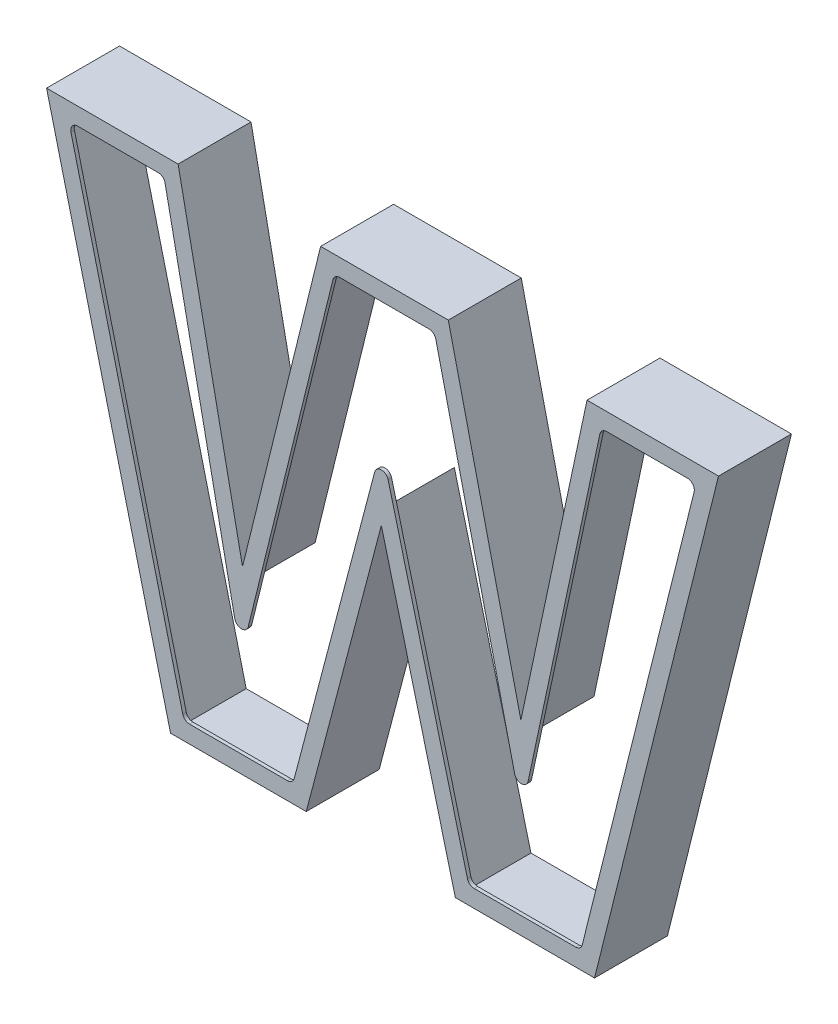
SolidWorks part; units mm, degrees
ref_plane "Front Plane" through (0, 0, 0) normal (0, 0, 1) x (1, 0, 0)
ref_plane "Top Plane" through (0, 0, 0) normal (0, 1, 0) x (1, 0, 0)
ref_plane "Right Plane" through (0, 0, 0) normal (1, 0, 0) x (0, 0, -1)
sketch "Sketch1" plane through (0, 0, 0) normal (0, 0, 1) x (1, 0, 0)
  line L104 (2646.8216, -1645.5826) -> (2668.4435, -1563.4302)
  line L105 (2668.4435, -1563.4302) -> (2689.75, -1645.5826)
  line L106 (2689.75, -1645.5826) -> (2729.8235, -1645.5826)
  line L107 (2729.8235, -1645.5826) -> (2765.5169, -1502.5826)
  line L108 (2765.5169, -1502.5826) -> (2727.6595, -1502.5826)
  line L109 (2727.6595, -1502.5826) -> (2708.6195, -1591.9057)
  line L110 (2708.6195, -1591.9057) -> (2687.7252, -1502.5826)
  line L111 (2687.7252, -1502.5826) -> (2650.9701, -1502.5826)
  line L112 (2650.9701, -1502.5826) -> (2628.4723, -1593.6985)
  line L113 (2628.4723, -1593.6985) -> (2609.9248, -1502.5826)
  line L114 (2609.9248, -1502.5826) -> (2572.0558, -1502.5826)
  line L115 (2572.0558, -1502.5826) -> (2607.7493, -1645.5826)
  line L116 (2607.7493, -1645.5826) -> (2646.8216, -1645.5826)
  line L117 (2646.8216, -1645.5826) -> (2668.4435, -1563.4302)
  line L118 (2668.4435, -1563.4302) -> (2689.75, -1645.5826)
  line L119 (2689.75, -1645.5826) -> (2729.8235, -1645.5826)
  line L120 (2729.8235, -1645.5826) -> (2765.5169, -1502.5826)
  line L121 (2765.5169, -1502.5826) -> (2727.6595, -1502.5826)
  line L122 (2727.6595, -1502.5826) -> (2708.6195, -1591.9057)
  line L123 (2708.6195, -1591.9057) -> (2687.7252, -1502.5826)
  line L124 (2687.7252, -1502.5826) -> (2650.9701, -1502.5826)
  line L125 (2650.9701, -1502.5826) -> (2628.4723, -1593.6985)
  line L126 (2628.4723, -1593.6985) -> (2609.9248, -1502.5826)
  line L127 (2609.9248, -1502.5826) -> (2572.0558, -1502.5826)
  line L128 (2572.0558, -1502.5826) -> (2607.7493, -1645.5826)
  line L129 (2607.7493, -1645.5826) -> (2646.8216, -1645.5826)
  dimension "D1" = 1.5
extrude "Boss-Extrude1" add sketch "Sketch1" against normal blind 20 and the other way blind 1
sketch3d "3DSketch1"
  line L0 (2690.5237, -1644.5826, -20) -> (2668.4506, -1559.4743, -20)
  line L1 (2668.4506, -1559.4743, -20) -> (2646.0508, -1644.5826, -20)
  line L2 (2646.0508, -1644.5826, -20) -> (2608.5303, -1644.5826, -20)
  line L3 (2608.5303, -1644.5826, -20) -> (2573.3361, -1503.5826, -20)
  line L4 (2573.3361, -1503.5826, -20) -> (2609.1078, -1503.5826, -20)
  line L5 (2609.1078, -1503.5826, -20) -> (2628.3784, -1598.2504, -20)
  line L6 (2628.3784, -1598.2504, -20) -> (2651.7532, -1503.5826, -20)
  line L7 (2651.7532, -1503.5826, -20) -> (2686.9321, -1503.5826, -20)
  line L8 (2686.9321, -1503.5826, -20) -> (2708.6648, -1596.4899, -20)
  line L9 (2708.6648, -1596.4899, -20) -> (2728.4688, -1503.5826, -20)
  line L10 (2728.4688, -1503.5826, -20) -> (2764.2367, -1503.5826, -20)
  line L11 (2764.2367, -1503.5826, -20) -> (2729.0424, -1644.5826, -20)
  line L12 (2729.0424, -1644.5826, -20) -> (2690.5237, -1644.5826, -20)
  line L13 (2690.5237, -1644.5826, -20) -> (2668.4506, -1559.4743, -20)
  line L14 (2668.4506, -1559.4743, -20) -> (2646.0508, -1644.5826, -20)
  line L15 (2646.0508, -1644.5826, -20) -> (2608.5303, -1644.5826, -20)
  line L16 (2608.5303, -1644.5826, -20) -> (2573.3361, -1503.5826, -20)
  line L17 (2573.3361, -1503.5826, -20) -> (2609.1078, -1503.5826, -20)
  line L18 (2609.1078, -1503.5826, -20) -> (2628.3784, -1598.2504, -20)
  line L19 (2628.3784, -1598.2504, -20) -> (2651.7532, -1503.5826, -20)
  line L20 (2651.7532, -1503.5826, -20) -> (2686.9321, -1503.5826, -20)
  line L21 (2686.9321, -1503.5826, -20) -> (2708.6648, -1596.4899, -20)
  line L22 (2708.6648, -1596.4899, -20) -> (2728.4688, -1503.5826, -20)
  line L23 (2728.4688, -1503.5826, -20) -> (2764.2367, -1503.5826, -20)
  line L24 (2764.2367, -1503.5826, -20) -> (2729.0424, -1644.5826, -20)
  line L25 (2729.0424, -1644.5826, -20) -> (2690.5237, -1644.5826, -20)
  dimension "D1" = 1
extrude "Cut-Extrude1" cut sketch "3DSketch1" along direction (0, 0, -1) on the side against the normal blind 20
sketch3d "3DSketch2"
  line L0 (2605.84, -1507.5826, 1) -> (2578.4573, -1507.5826, 1)
  line L1 (2578.4573, -1507.5826, 1) -> (2611.6547, -1640.5826, 1)
  line L2 (2611.6547, -1640.5826, 1) -> (2642.9673, -1640.5826, 1)
  line L3 (2642.9673, -1640.5826, 1) -> (2668.479, -1543.6507, 1)
  line L4 (2668.479, -1543.6507, 1) -> (2693.6187, -1640.5826, 1)
  line L5 (2693.6187, -1640.5826, 1) -> (2725.9181, -1640.5826, 1)
  line L6 (2725.9181, -1640.5826, 1) -> (2759.1155, -1507.5826, 1)
  line L7 (2759.1155, -1507.5826, 1) -> (2731.706, -1507.5826, 1)
  line L8 (2731.706, -1507.5826, 1) -> (2708.8461, -1614.8264, 1)
  line L9 (2708.8461, -1614.8264, 1) -> (2683.7598, -1507.5826, 1)
  line L10 (2683.7598, -1507.5826, 1) -> (2654.8857, -1507.5826, 1)
  line L11 (2654.8857, -1507.5826, 1) -> (2628.0028, -1616.4583, 1)
  line L12 (2628.0028, -1616.4583, 1) -> (2605.84, -1507.5826, 1)
  line L13 (2605.84, -1507.5826, 1) -> (2578.4573, -1507.5826, 1)
  line L14 (2578.4573, -1507.5826, 1) -> (2611.6547, -1640.5826, 1)
  line L15 (2611.6547, -1640.5826, 1) -> (2642.9673, -1640.5826, 1)
  line L16 (2642.9673, -1640.5826, 1) -> (2668.479, -1543.6507, 1)
  line L17 (2668.479, -1543.6507, 1) -> (2693.6187, -1640.5826, 1)
  line L18 (2693.6187, -1640.5826, 1) -> (2725.9181, -1640.5826, 1)
  line L19 (2725.9181, -1640.5826, 1) -> (2759.1155, -1507.5826, 1)
  line L20 (2759.1155, -1507.5826, 1) -> (2731.706, -1507.5826, 1)
  line L21 (2731.706, -1507.5826, 1) -> (2708.8461, -1614.8264, 1)
  line L22 (2708.8461, -1614.8264, 1) -> (2683.7598, -1507.5826, 1)
  line L23 (2683.7598, -1507.5826, 1) -> (2654.8857, -1507.5826, 1)
  line L24 (2654.8857, -1507.5826, 1) -> (2628.0028, -1616.4583, 1)
  line L25 (2628.0028, -1616.4583, 1) -> (2605.84, -1507.5826, 1)
  dimension "D1" = 5
extrude "Cut-Extrude2" cut sketch "3DSketch2" along direction (0, 0, -1) on the side against the normal through all
fillet "Fillet1" radius 2 13 edges
